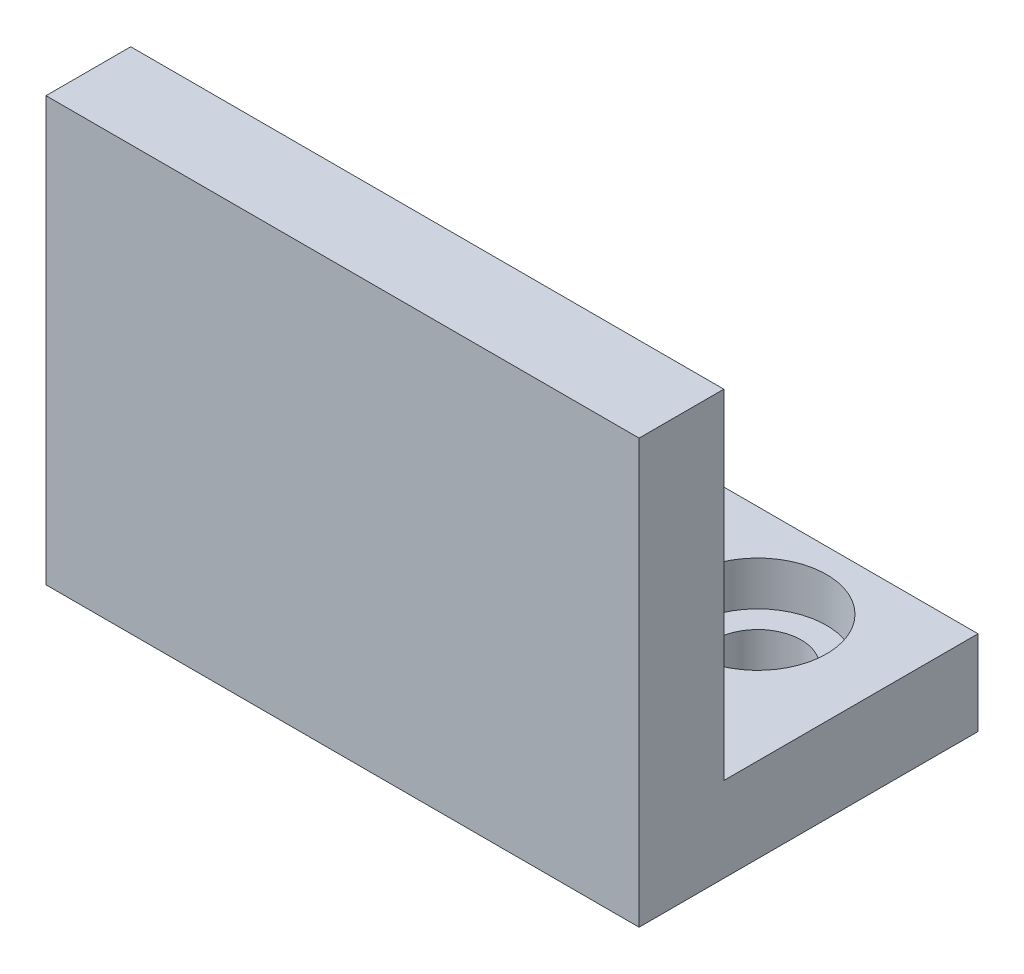
SolidWorks part; units mm, degrees
ref_plane "Front Plane" through (0, 0, 0) normal (0, 0, 1) x (1, 0, 0)
ref_plane "Top Plane" through (0, 0, 0) normal (0, 1, 0) x (1, 0, 0)
ref_plane "Right Plane" through (0, 0, 0) normal (1, 0, 0) x (0, 0, -1)
sketch "Sketch1" plane through (0, 0, 0) normal (1, 0, 0) x (0, 0, -1)
  line L0 (-25.4, 31.75) -> (-19.05, 31.75)
  line L1 (-19.05, 31.75) -> (-19.05, 6.35)
  line L2 (-19.05, 6.35) -> (0, 6.35)
  line L3 (0, 6.35) -> (0, 0)
  line L4 (13.97, 0) -> (-13.97, 0) construction
  line L5 (0, 0) -> (-25.4, 0)
  line L6 (-25.4, 0) -> (-25.4, 31.75)
  point P0 (41.4829, 0)
  point P10 (0, 0)
  dimension "D1" = 25.4
  dimension "D2" = 6.35
  dimension "D3" = 6.35
  dimension "D4" = 25.4
extrude "Boss-Extrude1" add sketch "Sketch1" along normal blind 44.45 contours L2 L3 L5 L6 L0 L1
sketch "Sketch2" plane through (0, 6.35, 0) normal (0, 1, 0) x (1, 0, 0)
  line L0 (9.525, -6.985) -> (34.925, -6.985) construction
  line L1 (44.45, -19.05) -> (0, -19.05) construction
  line L2 (44.45, -19.05) -> (0, -19.05) construction
  point P0 (9.525, -6.985)
  point P1 (34.925, -6.985)
  point P4 (22.225, -6.985)
  point P7 (22.225, -19.05)
  dimension "D1" = 25.4
  dimension "D2" = 12.065
hole_wizard "CBORE for 1/4 Socket Shoulder Screw1" positions "Sketch3" profile "Sketch4" counterbore size "1/4" standard "ANSI Inch" end condition through all
sketch "Sketch3" plane through (0, 6.35, 0) normal (0, 1, 0) x (1, 0, 0)
  point P0 (9.525, -6.985)
  point P3 (34.925, -6.985)
sketch "Sketch4" plane through (9.525, 6.35, 6.985) normal (1, 0, 0) x (0, 0, 1)
  line L0 (0, 0) -> (0, 6.35)
  line L1 (0, 6.35) -> (3.2639, 6.35)
  line L3 (3.2639, 6.35) -> (3.2639, 3.302)
  line L4 (3.2639, 3.302) -> (5.1587, 3.302)
  line L5 (5.1587, 3.302) -> (5.1587, 0)
  line L7 (5.1587, 0) -> (0, 0)
  line L11 (0, -6.35) -> (0, 107.95) construction
  dimension "Thru Hole Dia." = 6.5278
  dimension "Thru Hole Depth" = 6.35
  dimension "C'Bore Dia." = 10.3175
  dimension "C'Bore Depth" = 3.302
